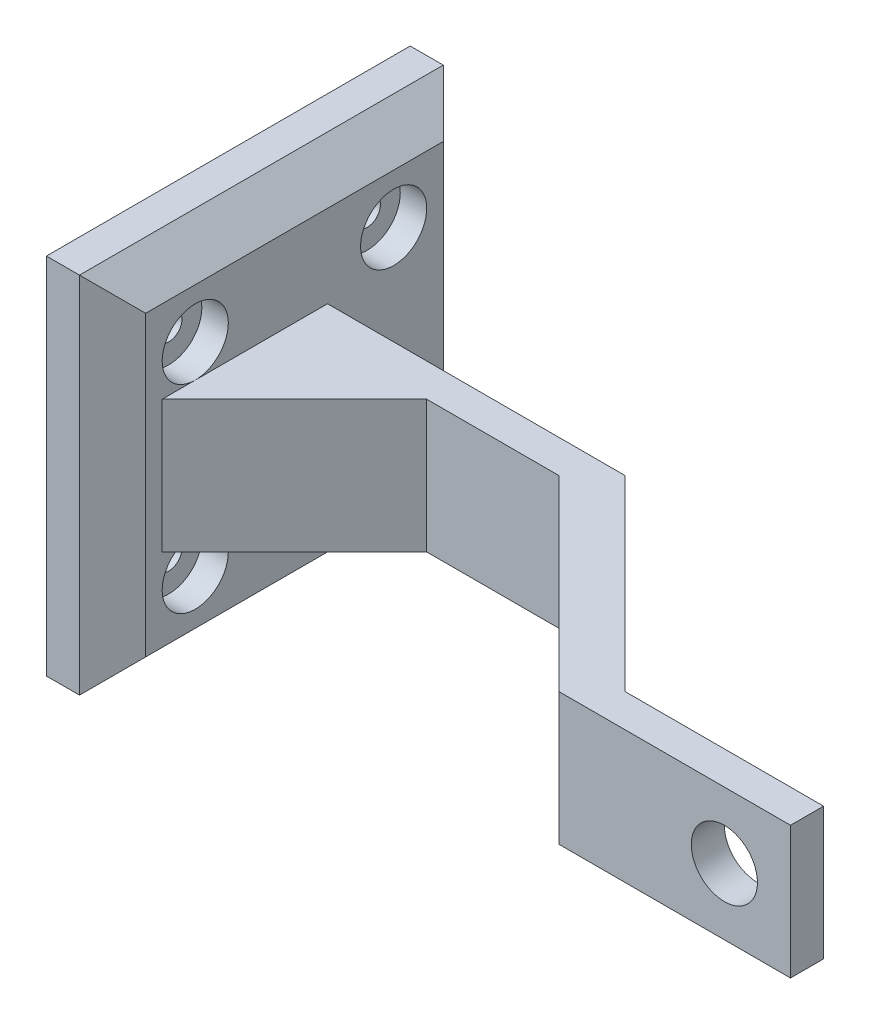
SolidWorks part; units mm, degrees
ref_plane "Front Plane" through (0, 0, 0) normal (0, 0, 1) x (1, 0, 0)
ref_plane "Top Plane" through (0, 0, 0) normal (0, 1, 0) x (1, 0, 0)
ref_plane "Right Plane" through (0, 0, 0) normal (1, 0, 0) x (0, 0, -1)
sketch "Sketch1" plane through (0, 0, 0) normal (0, 0, 1) x (1, 0, 0)
  line L1 (10, 10) -> (-10, 10)
  line L2 (10, 10) -> (10, -10)
  line L3 (10, -10) -> (-10, -10)
  line L4 (-10, 10) -> (-10, -10)
  line L5 (10, 10) -> (-10, -10) construction
  line L6 (10, -10) -> (-10, 10) construction
  circle A0 centre (0, 0) radius 5
  dimension "D1" = 10
  dimension "D2" = 20
  dimension "D3" = 20
extrude "Boss-Extrude1" add sketch "Sketch1" along normal blind 5
sketch "Sketch2" plane through (-10, 0, 0) normal (-1, 0, 0) x (0, 0, 1)
  line L4 (0, 10) -> (0, -10)
  line L5 (0, -10) -> (5, -10)
  line L6 (5, -10) -> (5, 10)
  line L7 (5, 10) -> (0, 10)
  line L8 (0, 10) -> (0, -10)
  line L9 (0, -10) -> (5, -10)
  line L10 (5, -10) -> (5, 10)
  line L11 (5, 10) -> (0, 10)
  dimension "D1" = 0
extrude "Boss-Extrude2" add sketch "Sketch2" along normal blind 15
sketch "Sketch3" plane through (0, -10, 0) normal (0, -1, 0) x (1, 0, 0)
  line L0 (-25, 5) -> (-20, 0)
  line L1 (-25, 5) -> (-53.2843, -23.2843)
  line L2 (-20, 0) -> (-48.2843, -28.2843)
  line L3 (-53.2843, -23.2843) -> (-48.2843, -28.2843)
  line L4 (-25, 0) -> (10, 0) construction
  line L6 (-48.2843, -28.2843) -> (-93.2843, -28.2843)
  line L7 (-48.2843, -28.2843) -> (-48.2843, -23.2843)
  line L8 (-48.2843, -23.2843) -> (-93.2843, -23.2843)
  line L9 (-93.2843, -28.2843) -> (-93.2843, -23.2843)
  line M5 (-25, 0) -> (10, 0)
  line M8 (-25, 5) -> (-25, 0)
  dimension "D1" = 5
  dimension "D2" = 40
  dimension "D3" = 5
  dimension "D4" = 45
extrude "Boss-Extrude3" add sketch "Sketch3" against normal up to surface (20 mm away) contours L8 L7 L2 L1 M5 M8 | L9 L6 L3 L8 | L7 L8 L3 up to face at (-7.5, 10, 2.5)
sketch "Sketch4" plane through (-93.2843, 0, 0) normal (-1, 0, 0) x (0, 0, 1)
  line L0 (-23.2843, 10) -> (-23.2843, -10) construction
  line L1 (4.2157, -27.5) -> (-50.7843, -27.5)
  line L2 (4.2157, -27.5) -> (4.2157, 27.5)
  line L3 (4.2157, 27.5) -> (-50.7843, 27.5)
  line L4 (-50.7843, -27.5) -> (-50.7843, 27.5)
  line L5 (4.2157, -27.5) -> (-50.7843, 27.5) construction
  line L6 (4.2157, 27.5) -> (-50.7843, -27.5) construction
  point P0 (-23.2843, 0)
  dimension "D1" = 55
  dimension "D2" = 55
extrude "Boss-Extrude4" add sketch "Sketch4" along normal blind 10
chamfer "Chamfer1" distance 20 angle 45 1 edges at (-93.2843, 0, -23.2843)
chamfer "Chamfer2" distance 5 angle 45 4 edges at (-93.2843, 0, 4.2157) (-93.2843, 27.5, -23.2843) (-93.2843, 0, -50.7843) (-93.2843, -27.5, -23.2843)
sketch "Sketch5" plane through (-93.2843, 0, 0) normal (1, 0, 0) x (0, 0, -1)
  line L0 (45.7843, 0) -> (22.6508, 0) construction
  line L1 (45.7843, -22.5) -> (45.7843, 22.5) construction
  line L2 (45.7843, 0) -> (0.7843, 0) construction
  line L3 (0.7843, 22.5) -> (0.7843, -22.5) construction
  line L4 (0.7843, 0) -> (23.2843, 0) construction
  line L5 (23.2843, 0) -> (23.2843, 16.0216) construction
  circle A0 centre (38.2843, 15) radius 2
  circle A1 centre (38.2843, -15) radius 2
  circle A2 centre (8.2843, -15) radius 2
  circle A3 centre (8.2843, 15) radius 2
  dimension "D1" = 4
  dimension "D2" = 15
  dimension "D3" = 15
extrude "Cut-Extrude1" cut sketch "Sketch5" against normal through all
sketch "Sketch6" plane through (-93.2843, 0, 0) normal (1, 0, 0) x (0, 0, -1)
  circle A0 centre (38.2843, 15) radius 2 construction
  circle A1 centre (38.2843, -15) radius 2 construction
  circle A3 centre (8.2843, 15) radius 2 construction
  circle A6 centre (8.2843, -15) radius 2 construction
  circle A18 centre (8.2843, 15) radius 2
  circle A19 centre (8.2843, -15) radius 2
  circle A20 centre (38.2843, -15) radius 2
  circle A21 centre (38.2843, 15) radius 2
  circle A22 centre (8.2843, 15) radius 5
  circle A23 centre (8.2843, -15) radius 5
  circle A24 centre (38.2843, -15) radius 5
  circle A25 centre (38.2843, 15) radius 5
  dimension "D1" = 3
extrude "Cut-Extrude2" cut sketch "Sketch6" against normal blind 4
